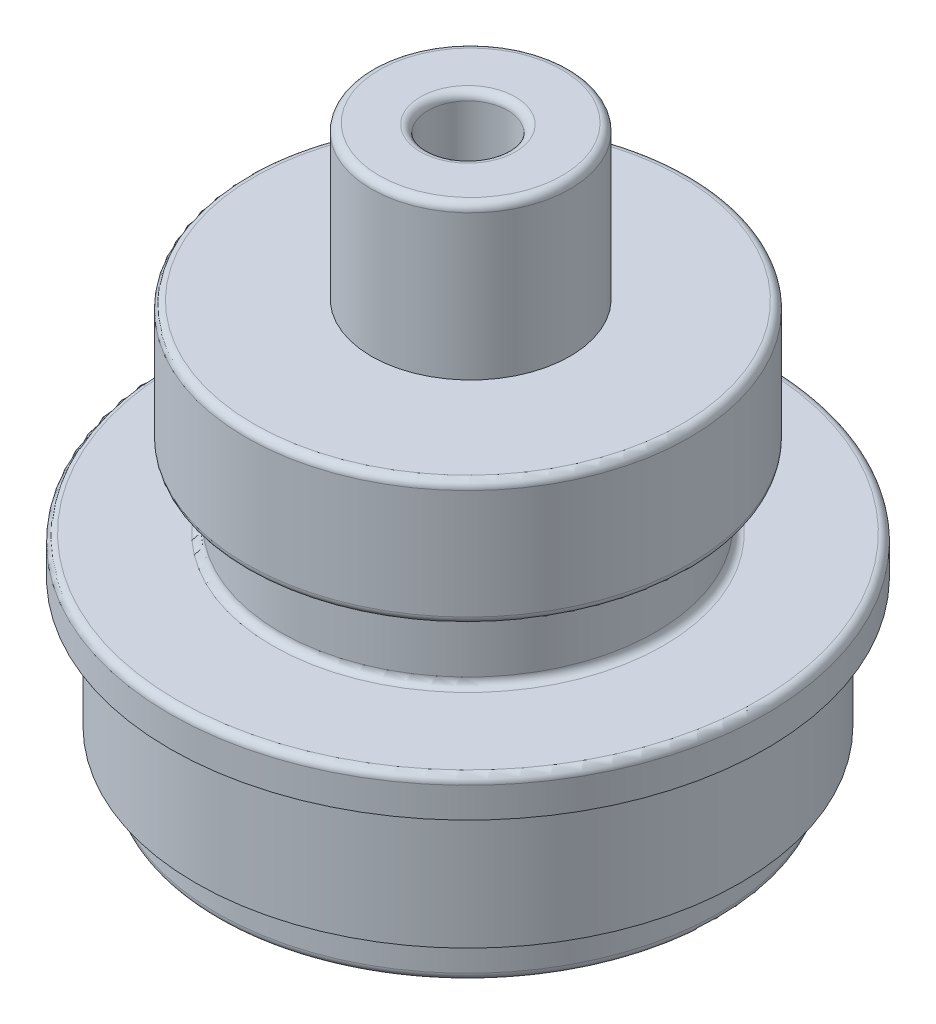
SolidWorks part; units mm, degrees
ref_plane "Front Plane" through (0, 0, 0) normal (0, 0, 1) x (1, 0, 0)
ref_plane "Top Plane" through (0, 0, 0) normal (0, 1, 0) x (1, 0, 0)
ref_plane "Right Plane" through (0, 0, 0) normal (1, 0, 0) x (0, 0, -1)
sketch "Sketch1" plane through (0, 0, 0) normal (0, 1, 0) x (1, 0, 0)
  circle A0 centre (0, 0) radius 38.1
extrude "Boss-Extrude4" add sketch "Sketch1" along normal blind 4.8514
sketch "Sketch5" plane through (0, 4.8514, 0) normal (0, 1, 0) x (1, 0, 0)
  circle A0 centre (0, 0) radius 23.9776
extrude "Boss-Extrude5" add sketch "Sketch5" along normal blind 9.7282
sketch "Sketch6" plane through (0, 14.5796, 0) normal (0, 1, 0) x (1, 0, 0)
  circle A0 centre (0, 0) radius 28.3464
extrude "Boss-Extrude6" add sketch "Sketch6" along normal blind 16.002
sketch "Sketch7" plane through (0, 30.5816, 0) normal (0, 1, 0) x (1, 0, 0)
  circle A0 centre (0, 0.353) radius 12.7
extrude "Boss-Extrude7" add sketch "Sketch7" along normal blind 19.5072
sketch "Sketch8" plane through (0, 0, 0) normal (0, -1, 0) x (1, 0, 0)
  circle A0 centre (0, 0) radius 34.798
extrude "Boss-Extrude8" add sketch "Sketch8" along normal blind 16.51
sketch "Sketch9" plane through (0, -16.51, 0) normal (0, -1, 0) x (1, 0, 0)
  circle A0 centre (0, 0) radius 32.0675
extrude "Boss-Extrude9" add sketch "Sketch9" along normal blind 5.715
sketch "Sketch10" plane through (0, -22.225, 0) normal (0, -1, 0) x (1, 0, 0)
  circle A0 centre (0, 0) radius 19.05
extrude "Cut-Extrude1" cut sketch "Sketch10" against normal blind 38.1
sketch "Sketch11" plane through (0, 50.0888, 0) normal (0, 1, 0) x (1, 0, 0)
  circle A0 centre (0, 0) radius 5.08
extrude "Cut-Extrude2" cut sketch "Sketch11" against normal blind 29.718
fillet "Fillet1" radius 1 9 edges at (0, -22.225, -19.05) (0, -22.225, -32.0675) (0, 50.0888, 5.08) (0, 4.8514, 38.1) (0, 4.8514, 23.9776) (0, 14.5796, 23.9776) (0, 14.5796, 28.3464) (0, 30.5816, 28.3464) (0, 50.0888, 12.347)
